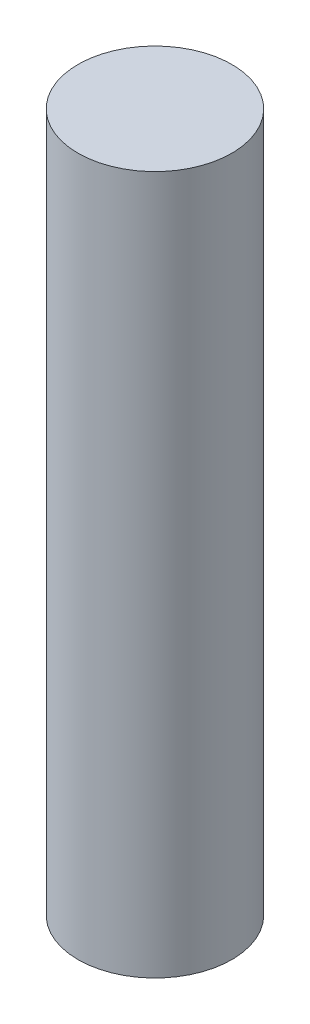
SolidWorks part; units mm, degrees
ref_plane "Front Plane" through (0, 0, 0) normal (0, 0, 1) x (1, 0, 0)
ref_plane "Top Plane" through (0, 0, 0) normal (0, 1, 0) x (1, 0, 0)
ref_plane "Right Plane" through (0, 0, 0) normal (1, 0, 0) x (0, 0, -1)
sketch "Sketch2" plane through (0, 0, 0) normal (0, 1, 0) x (1, 0, 0)
  circle A0 centre (0, 0) radius 10.795
  dimension "D1" = 21.59
extrude "Boss-Extrude1" add sketch "Sketch2" along normal blind 98
